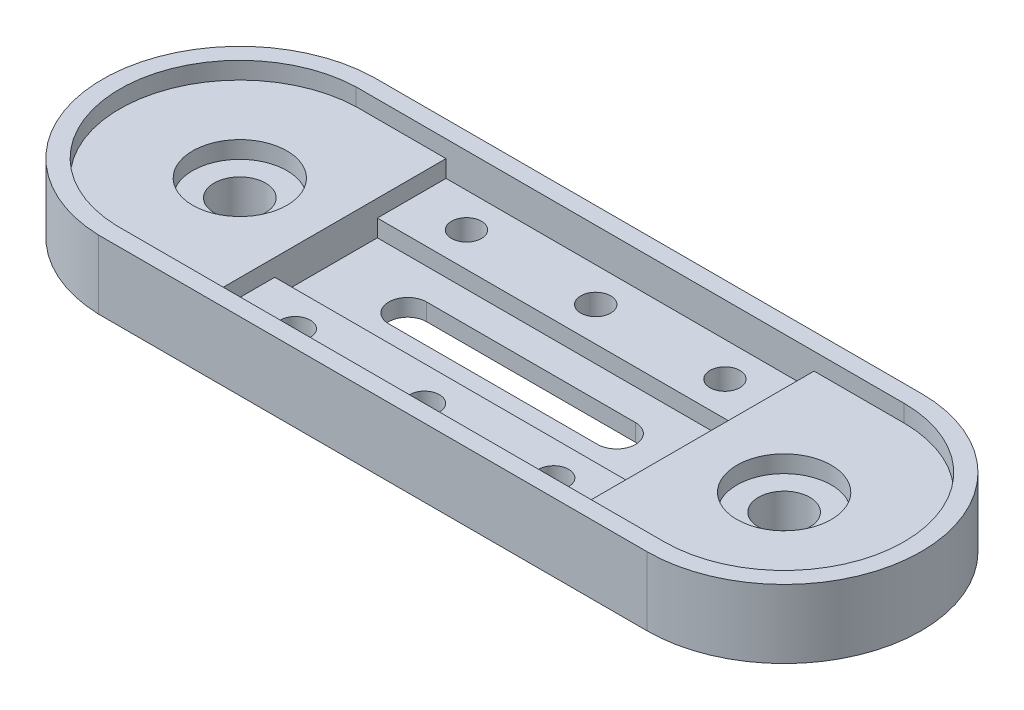
SolidWorks part; units mm, degrees
ref_plane "Front Plane" through (0, 0, 0) normal (0, 0, 1) x (1, 0, 0)
ref_plane "Top Plane" through (0, 0, 0) normal (0, 1, 0) x (1, 0, 0)
ref_plane "Right Plane" through (0, 0, 0) normal (1, 0, 0) x (0, 0, -1)
sketch "Sketch1" plane through (0, 0, 0) normal (0, 1, 0) x (1, 0, 0)
  line L1 (0, 0) -> (101.6, 0)
  line L3 (0, 50.8) -> (101.6, 50.8)
  arc A0 (0, 50.8) -> (0, 0) centre (0.7457, 25.4) ccw
  arc A1 (101.6, 0) -> (101.6, 50.8) centre (101.6, 25.4) ccw
extrude "Extrude1" add sketch "Sketch1" against normal blind 12.7
sketch "Sketch2" plane through (0, 0, 0) normal (0, 1, 0) x (1, 0, 0)
  line L0 (50.8, 0) -> (50.8, 50.8) construction
  line L1 (101.6, 47.625) -> (0.0482, 47.625)
  line L2 (0.0482, 3.175) -> (101.6, 3.175)
  line L3 (0, 0) -> (101.6, 0) construction
  line L4 (101.6, 50.8) -> (0, 50.8) construction
  arc A0 (0.0482, 47.625) -> (0.0482, 3.175) centre (0.7457, 25.4) ccw
  arc A1 (101.6, 3.175) -> (101.6, 47.625) centre (101.6, 25.4) ccw
extrude "Extrude2" cut sketch "Sketch2" against normal blind 3.175
ref_plane "Plane1" through (0, -3.175, 0) normal (0, 1, 0) x (-1, 0, 0)
sketch "Sketch3" plane through (0, -3.175, 0) normal (0, 1, 0) x (-1, 0, 0)
  line L3 (-0.0482, -3.175) -> (-101.6, -3.175) construction
  line L6 (-16.7285, -47.625) -> (-84.9196, -47.625)
  line L7 (-16.7285, -47.625) -> (-16.7285, -3.175)
  line L8 (-16.7285, -3.175) -> (-84.9196, -3.175)
  line L9 (-84.9196, -47.625) -> (-84.9196, -3.175)
  point P6 (-50.8241, -25.4)
extrude "Extrude3" cut sketch "Sketch3" against normal blind 3.175
ref_plane "Plane2" through (0, -6.35, 0) normal (0, 1, 0) x (-1, 0, 0)
sketch "Sketch4" plane through (0, -6.35, 0) normal (0, 1, 0) x (-1, 0, 0)
  line L0 (-50.8241, -47.625) -> (-50.8241, -3.175) construction
  line L1 (-84.9196, -47.625) -> (-16.7285, -47.625) construction
  line L2 (-16.7285, -3.175) -> (-84.9196, -3.175) construction
  line L3 (-84.9196, -3.175) -> (-84.9196, -47.625) construction
  line L4 (-16.7285, -34.9028) -> (-84.9196, -34.9028)
  line L5 (-16.7285, -34.9028) -> (-16.7285, -15.8972)
  line L6 (-16.7285, -15.8972) -> (-84.9196, -15.8972)
  line L7 (-84.9196, -34.9028) -> (-84.9196, -15.8972)
  point P6 (-50.8241, -25.4)
extrude "Extrude4" cut sketch "Sketch4" against normal blind 3.175
sketch "Sketch6" plane through (0, -6.35, 0) normal (0, 1, 0) x (-1, 0, 0)
  line L1 (-70.2867, -22.1571) -> (-31.5855, -22.1571)
  line L3 (-70.2867, -29.1792) -> (-31.5855, -29.1792)
  arc A0 (-31.5855, -29.1792) -> (-31.5855, -22.1571) centre (-31.5855, -25.6681) ccw
  arc A1 (-70.2867, -22.1571) -> (-70.2867, -29.1792) centre (-70.2867, -25.6681) ccw
  point P0 (-50.9361, -25.6681)
extrude "Extrude6" cut sketch "Sketch6" against normal through all
sketch "Sketch10" plane through (0, -3.175, 0) normal (0, 1, 0) x (-1, 0, 0)
  point P0 (-101.6, -25.4)
  point P1 (-0.7457, -25.4)
hole_wizard "CBORE for 1/4 Binding Head Machine Screw2" positions "Sketch12" profile "Sketch11" counterbore size "1/4" standard "Ansi Inch" end condition through all
sketch "Sketch12" plane through (0, -3.175, 0) normal (0, 1, 0) x (-1, 0, 0)
  point P0 (-0.7457, -25.4)
  point P1 (-101.6, -25.4)
sketch "Sketch11" plane through (0.7457, -3.175, -25.4) normal (1, 0, 0) x (0, 0, 1)
  line L0 (0, 0) -> (0, 9.525)
  line L1 (0, 9.525) -> (4.7625, 9.525)
  line L3 (4.7625, 9.525) -> (4.7625, 3.175)
  line L4 (4.7625, 3.175) -> (8.7376, 3.175)
  line L5 (8.7376, 3.175) -> (8.7376, 0)
  line L7 (8.7376, 0) -> (0, 0)
  line L11 (0, -6.35) -> (0, 107.95) construction
  dimension "Thru Hole Dia." = 9.525
  dimension "Thru Hole Depth" = 9.525
  dimension "C'Bore Dia." = 17.4752
  dimension "C'Bore Depth" = 3.175
ref_plane "Plane3" through (0, -6.35, 0) normal (0, 1, 0) x (-1, 0, 0)
sketch "Sketch13" plane through (0, -6.35, 0) normal (0, 1, 0) x (-1, 0, 0)
  line L3 (-74.7657, -41.2639) -> (-74.7657, -34.9028) construction
  line L5 (-26.8825, -41.2639) -> (-26.8825, -34.9028) construction
  line L6 (-84.9196, -34.9028) -> (-16.7285, -34.9028) construction
  line L7 (-50.8241, -41.2639) -> (-50.8241, -34.9028) construction
  line L8 (-50.8241, -9.5361) -> (-50.8241, -15.8972) construction
  line L9 (-74.7657, -9.5361) -> (-74.7657, -15.8972) construction
  line L10 (-16.7285, -15.8972) -> (-84.9196, -15.8972) construction
  line L11 (-26.8825, -9.5361) -> (-26.8825, -15.8972) construction
hole_wizard "7/32 (0.21875) Diameter Hole1" positions "Sketch17" profile "Sketch16" hole size "7/32" standard "Ansi Inch"
sketch "Sketch17" plane through (0, -6.35, 0) normal (0, 1, 0) x (-1, 0, 0)
  point P0 (-26.8825, -9.5361)
sketch "Sketch16" plane through (26.8825, -6.35, -9.5361) normal (1, 0, 0) x (0, 0, 1)
  line L0 (0, 0) -> (0, 27.0693)
  line L1 (0, 27.0693) -> (2.7781, 25.4)
  line L2 (2.7781, 25.4) -> (2.7781, 0)
  line L5 (2.7781, 0) -> (0, 0)
  line L10 (0, 27.0693) -> (-2.7781, 25.4) construction
  line L11 (0, -6.35) -> (0, 107.95) construction
  dimension "Hole Dia." = 5.5562
  dimension "Hole Depth" = 25.4
  dimension "Drill Angle" = 118
hole_wizard "7/32 (0.21875) Diameter Hole2" positions "Sketch19" profile "Sketch18" hole size "7/32" standard "Ansi Inch"
sketch "Sketch19" plane through (0, -6.35, 0) normal (0, 1, 0) x (-1, 0, 0)
  point P0 (-50.8241, -9.5361)
  point P1 (-74.7657, -9.5361)
  point P4 (-26.8825, -41.2639)
  point P7 (-50.8241, -41.2639)
  point P10 (-74.7657, -41.2639)
sketch "Sketch18" plane through (50.8241, -6.35, -9.5361) normal (1, 0, 0) x (0, 0, 1)
  line L0 (0, 0) -> (0, 27.0693)
  line L1 (0, 27.0693) -> (2.7781, 25.4)
  line L2 (2.7781, 25.4) -> (2.7781, 0)
  line L5 (2.7781, 0) -> (0, 0)
  line L10 (0, 27.0693) -> (-2.7781, 25.4) construction
  line L11 (0, -6.35) -> (0, 107.95) construction
  dimension "Hole Dia." = 5.5562
  dimension "Hole Depth" = 25.4
  dimension "Drill Angle" = 118
